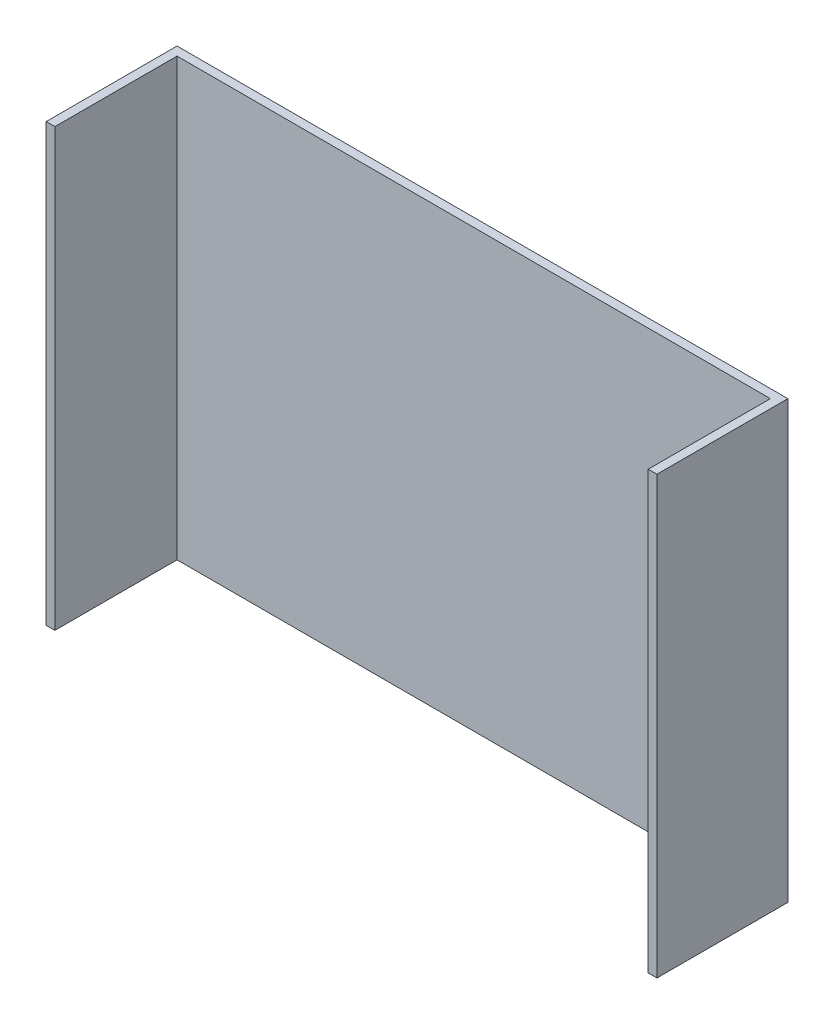
SolidWorks part; units mm, degrees
ref_plane "前基準面" through (0, 0, 0) normal (0, 0, 1) x (1, 0, 0)
ref_plane "上基準面" through (0, 0, 0) normal (0, 1, 0) x (1, 0, 0)
ref_plane "右基準面" through (0, 0, 0) normal (1, 0, 0) x (0, 0, -1)
sketch "草圖1" plane through (0, 0, 0) normal (0, 0, 1) x (1, 0, 0)
  line L1 (0, 0) -> (-140, 0)
  line L2 (0, 0) -> (0, 100)
  line L3 (0, 100) -> (-140, 100)
  line L4 (-140, 0) -> (-140, 100)
  dimension "D1" = 140
  dimension "D2" = 100
extrude "填料-伸長1" add sketch "草圖1" along normal blind 30
sketch "草圖2" plane through (0, 0, 30) normal (0, 0, 1) x (1, 0, 0)
  line L0 (-140, 0) -> (0, 0) construction
  line L1 (-138, 0) -> (-2, 0)
  line L2 (-138, 0) -> (-138, 100)
  line L3 (-138, 100) -> (-2, 100)
  line L4 (-2, 0) -> (-2, 100)
  line L5 (-140, 100) -> (-140, 0) construction
  dimension "D1" = 100
  dimension "D2" = 0
  dimension "D3" = 2
  dimension "D4" = 136
extrude "除料-伸長1" cut sketch "草圖2" against normal blind 28
